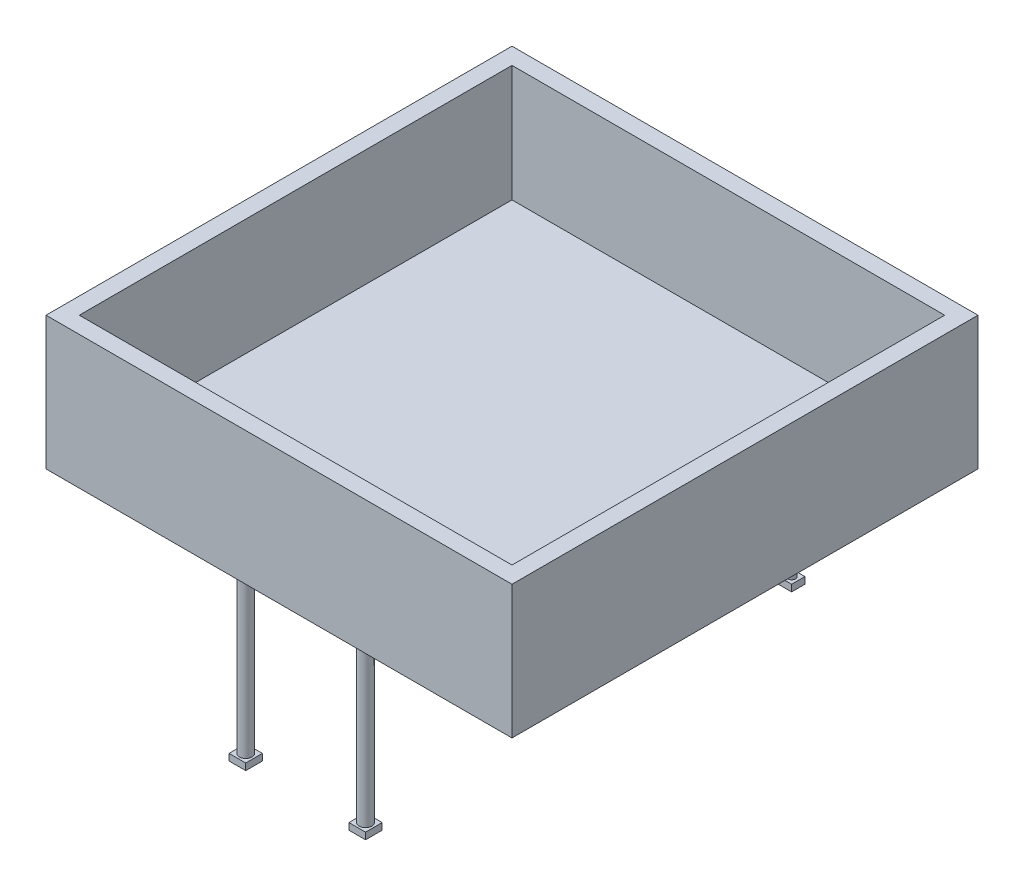
SolidWorks part; units mm, degrees
ref_plane "Alzado" through (0, 0, 0) normal (0, 0, 1) x (1, 0, 0)
ref_plane "Planta" through (0, 0, 0) normal (0, 1, 0) x (1, 0, 0)
ref_plane "Vista lateral" through (0, 0, 0) normal (1, 0, 0) x (0, 0, -1)
sketch "Croquis1" plane through (0, 0, 0) normal (0, 1, 0) x (1, 0, 0)
  line L1 (70, -70) -> (-70, -70)
  line L2 (70, -70) -> (70, 70)
  line L3 (70, 70) -> (-70, 70)
  line L4 (-70, -70) -> (-70, 70)
  line L5 (70, -70) -> (-70, 70) construction
  line L6 (70, 70) -> (-70, -70) construction
  point P0 (0, 0)
  dimension "D1" = 140
  dimension "D2" = 140
extrude "Saliente-Extruir1" add sketch "Croquis1" along normal blind 40
sketch "Croquis3" plane through (0, 40, 0) normal (0, 1, 0) x (1, 0, 0)
  line L8 (-65, 65) -> (-65, -65)
  line L9 (-65, -65) -> (65, -65)
  line L10 (65, -65) -> (65, 65)
  line L11 (65, 65) -> (-65, 65)
  line L12 (-65, 65) -> (-65, -65)
  line L13 (-65, -65) -> (65, -65)
  line L14 (65, -65) -> (65, 65)
  line L15 (65, 65) -> (-65, 65)
  dimension "D1" = 5
extrude "Cortar-Extruir1" cut sketch "Croquis3" against normal blind 35
sketch "Croquis4" plane through (0, 0, 0) normal (0, 0, 1) x (1, 0, 0)
  line L0 (-31.4496, 0) -> (-23.2248, 0)
  line L3 (-23.45, -15) -> (-31.45, -15)
  line L4 (-31.45, -15) -> (-31.4496, 0)
  line L5 (0, -3.0023) -> (0, 8.1119) construction
  line L13 (-23.2248, 3.186) -> (-23.2248, -4.5966) construction
  line L15 (-23.2248, 0) -> (-23.45, -15)
  dimension "D1" = 8
  dimension "D4" = 15
sketch "Croquis5" plane through (0, 0, 0) normal (0, -1, 0) x (1, 0, 0)
  line L0 (0, 17.425) -> (0, -13.0916) construction
  line L2 (-16, 64) -> (-16, -64) construction
  line L3 (20, 64) -> (20, -64) construction
  circle A2 centre (-16, -64) radius 1.2
  circle A3 centre (-16, 64) radius 1.9
  circle A4 centre (20, 64) radius 1.9
  circle A5 centre (20, -64) radius 1.2
  point P4 (0, 0)
  point P10 (-16, 0)
  dimension "D1" = 2.4
  dimension "D2" = 3.8
  dimension "D3" = 128
  dimension "D4" = 36
  dimension "D5" = 36
extrude "Saliente-Extruir4" add sketch "Croquis5" along normal blind 50
sketch "Croquis6" plane through (0, -50, 0) normal (0, -1, 0) x (1, 0, 0)
  line L1 (-13.5, 61.5) -> (-18.5, 61.5)
  line L2 (-13.5, 61.5) -> (-13.5, 66.5)
  line L3 (-13.5, 66.5) -> (-18.5, 66.5)
  line L4 (-18.5, 61.5) -> (-18.5, 66.5)
  line L5 (-13.5, 61.5) -> (-18.5, 66.5) construction
  line L6 (-13.5, 66.5) -> (-18.5, 61.5) construction
  line L7 (22.5, 66.5) -> (17.5, 66.5)
  line L8 (22.5, 66.5) -> (22.5, 61.5)
  line L9 (22.5, 61.5) -> (17.5, 61.5)
  line L10 (17.5, 66.5) -> (17.5, 61.5)
  line L11 (22.5, 66.5) -> (17.5, 61.5) construction
  line L12 (22.5, 61.5) -> (17.5, 66.5) construction
  line L13 (-14, -66) -> (-18, -66)
  line L14 (-14, -66) -> (-14, -62)
  line L15 (-14, -62) -> (-18, -62)
  line L16 (-18, -66) -> (-18, -62)
  line L17 (-14, -66) -> (-18, -62) construction
  line L18 (-14, -62) -> (-18, -66) construction
  line L19 (22, -66) -> (18, -66)
  line L20 (22, -66) -> (22, -62)
  line L21 (22, -62) -> (18, -62)
  line L22 (18, -66) -> (18, -62)
  line L23 (22, -66) -> (18, -62) construction
  line L24 (22, -62) -> (18, -66) construction
  point P0 (-16, 64)
  point P6 (20, 64)
  point P12 (-16, -64)
  point P17 (-16, -64)
  point P18 (-16, -64)
  point P19 (20, -64)
  point P25 (20, -64)
  dimension "D1" = 5
  dimension "D2" = 5
  dimension "D3" = 5
  dimension "D4" = 5
  dimension "D5" = 4
  dimension "D6" = 4
  dimension "D7" = 4
  dimension "D8" = 4
extrude "Saliente-Extruir5" add sketch "Croquis6" along normal blind 2
